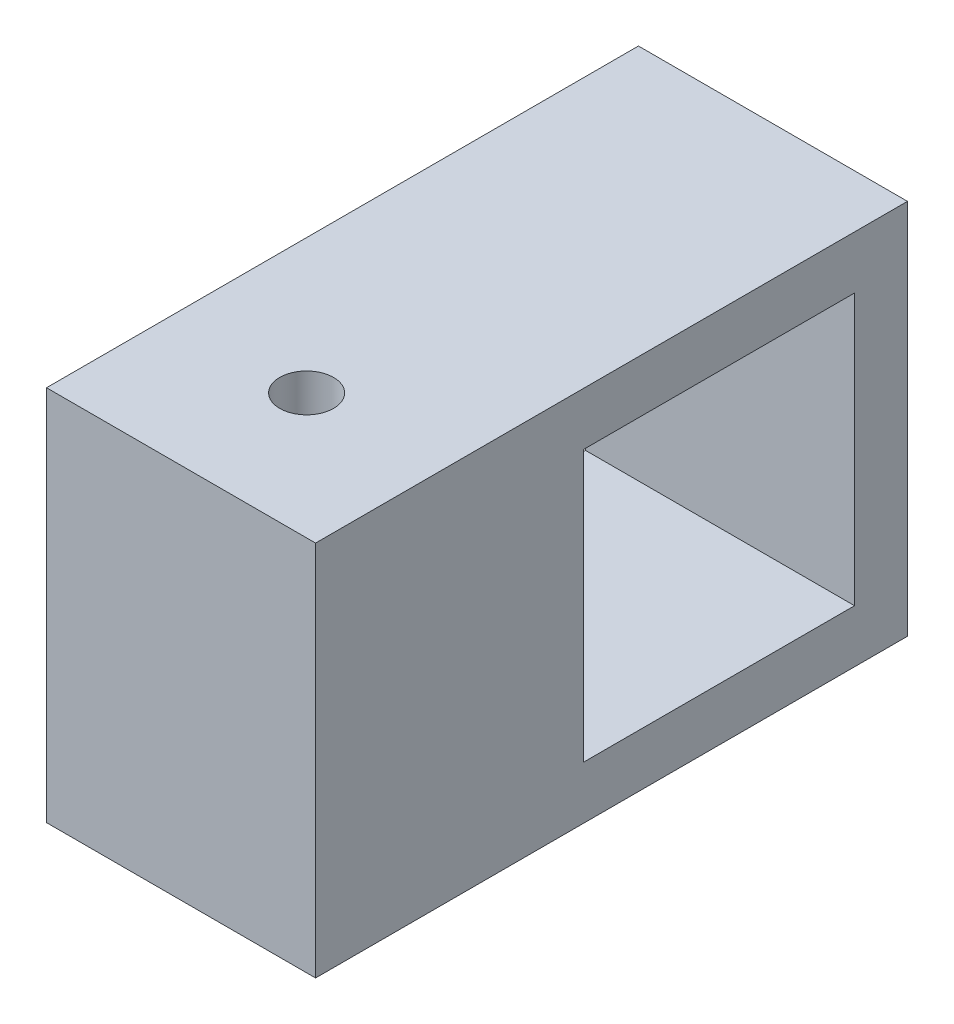
SolidWorks part; units mm, degrees
ref_plane "Piano frontale" through (0, 0, 0) normal (0, 0, 1) x (1, 0, 0)
ref_plane "Piano superiore" through (0, 0, 0) normal (0, 1, 0) x (1, 0, 0)
ref_plane "Piano destro" through (0, 0, 0) normal (1, 0, 0) x (0, 0, -1)
sketch "Schizzo1" plane through (0, 0, 0) normal (1, 0, 0) x (0, 0, -1)
  line L0 (-10.5, 10.5) -> (-22.5, 10.5)
  line L1 (-10.5, -10.5) -> (10.5, -10.5)
  line L2 (-10.5, -10.5) -> (-10.5, 10.5)
  line L3 (-10.5, 10.5) -> (10.5, 10.5)
  line L4 (10.5, -10.5) -> (10.5, 10.5)
  line L5 (-10.5, -10.5) -> (10.5, 10.5) construction
  line L6 (-10.5, 10.5) -> (10.5, -10.5) construction
  line L7 (-7.55, -7.55) -> (7.55, -7.55)
  line L8 (-7.55, -7.55) -> (-7.55, 7.55)
  line L9 (-7.55, 7.55) -> (7.55, 7.55)
  line L10 (7.55, -7.55) -> (7.55, 7.55)
  line L11 (-7.55, -7.55) -> (7.55, 7.55) construction
  line L12 (-7.55, 7.55) -> (7.55, -7.55) construction
  line L13 (-22.5, 10.5) -> (-22.5, -10.5)
  line L14 (-22.5, -10.5) -> (-10.5, -10.5)
  point P0 (0, 0)
  point P6 (0, 0)
  dimension "D1" = 21
  dimension "D2" = 15.1
  dimension "D3" = 21
  dimension "D4" = 15.1
  dimension "D5" = 12
extrude "Estrusione-Estrusione1" add sketch "Schizzo1" along normal blind 15 contours L13 L14 L2 L0 | L1 L4 L3 L2 L10 L7 L8 L9
sketch "Schizzo2" plane through (0, 10.5, 0) normal (0, 1, 0) x (1, 0, 0)
  line L0 (15, 10.5) -> (15, -22.5) construction
  line L1 (15, -22.5) -> (0, -22.5) construction
  circle A0 centre (7.5, -15.5) radius 1.5
  dimension "D1" = 7.5
  dimension "D2" = 7
  dimension "D3" = 3
extrude "Taglio-Estrusione1" cut sketch "Schizzo2" along direction (0, 1, 0) on the side against the normal blind 15
sketch "Schizzo3" plane through (0, -10.5, 0) normal (0, -1, 0) x (1, 0, 0)
  line L0 (15, 22.5) -> (15, -10.5) construction
  line L1 (15, 22.5) -> (0, 22.5) construction
  circle A0 centre (7.5, 19.5) radius 1.5
  dimension "D1" = 3
  dimension "D2" = 7.5
  dimension "D3" = 3
extrude "Taglio-Estrusione2" cut sketch "Schizzo3" against normal blind 15
